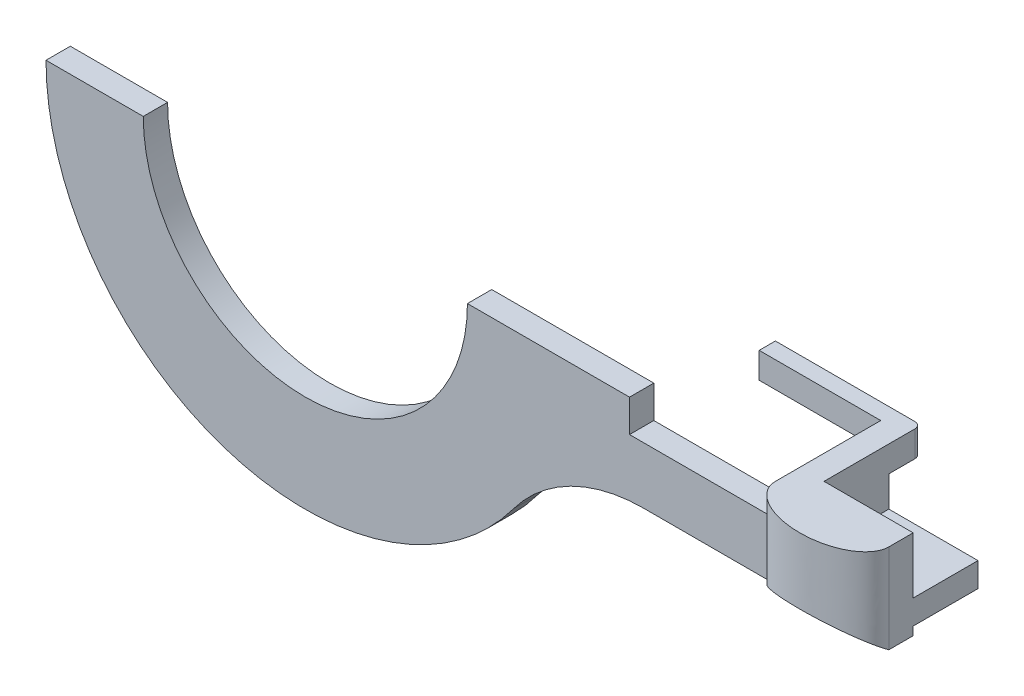
SolidWorks part; units mm, degrees
ref_plane "Face" through (0, 0, 0) normal (0, 0, 1) x (1, 0, 0)
ref_plane "Dessus" through (0, 0, 0) normal (0, 1, 0) x (1, 0, 0)
ref_plane "Droite" through (0, 0, 0) normal (1, 0, 0) x (0, 0, -1)
sketch "Esquisse1" plane through (0, 0, 0) normal (0, 0, 1) x (1, 0, 0)
  line L0 (0, 0) -> (34.0307, 0) construction
  line L1 (10.4373, -2.75) -> (18, -2.75)
  line L2 (10.4373, 2.75) -> (18, 2.75)
  line L3 (18, 2.75) -> (18, -2.75)
  line L4 (10, 1) -> (14.5, 1)
  line L5 (10, -1) -> (14.5, -1)
  line L6 (10, 1) -> (10, -1)
  line L7 (14.5, 1) -> (14.5, -1)
  circle A0 centre (0, 0) radius 5
  arc A1 (6.423, 4.7692) -> (6.423, -4.7692) centre (0, 0) ccw
  arc A2 (6.423, 4.7692) -> (10.4373, 2.75) centre (10.4373, 7.75) ccw
  arc A3 (6.423, -4.7692) -> (10.4373, -2.75) centre (10.4373, -7.75) cw
  point P10 (7.5125, 2.75)
  point P13 (7.5125, -2.75)
  dimension "D1" = 10
  dimension "D2" = 16
  dimension "D4" = 5
  dimension "D3" = 18
  dimension "D5" = 2
  dimension "D6" = 3.5
  dimension "D7" = 4.5
  dimension "D8" = 5.5
extrude "Base-Extrusion" add sketch "Esquisse1" along normal blind 0.75
sketch "Esquisse2" plane through (0, 0, 0) normal (0, 1, 0) x (1, 0, 0)
  line L1 (14.5, -0.75) -> (18, -0.75)
  line L2 (16.25, -0.75) -> (16.25, -1.75) construction
  ellipse E0 centre (16.25, -0.75) end of major axis (18, -0.75) minor radius 1 (14.5, -0.75) -> (18, -0.75) ccw
  dimension "D1" = 1
extrude "Boss.-Extru.1" add sketch "Esquisse2" against normal mid plane 5.5
sketch "Esquisse3" plane through (0, 0, 0) normal (0, 0, -1) x (-1, 0, 0)
  line L0 (-14.1992, 0.0087) -> (-18.5439, 0.0087) construction
  line L1 (-18, 2.5087) -> (-14.5, 2.5087)
  line L2 (-14.5, -1) -> (-14.5, 1) construction
  line L3 (-14.5, -2.4913) -> (-14.5, 2.5087)
  line L4 (-18, -2.75) -> (-18, 2.75) construction
  line L5 (-18, -2.4913) -> (-18, -1.7413)
  line L6 (-18, -2.4913) -> (-14.5, -2.4913)
  line L7 (-18, -1.7413) -> (-15.25, -1.7413)
  line L8 (-15.25, -1.7413) -> (-15.25, 1.7587)
  line L9 (-18, 1.7587) -> (-15.25, 1.7587)
  line L10 (-18, 1.7587) -> (-18, 2.5087)
  dimension "D1" = 5
  dimension "D2" = 0.75
extrude "Boss.-Extru.2" add sketch "Esquisse3" along normal blind 2
sketch "Esquisse4" plane through (0, 0, -2) normal (0, 0, -1) x (-1, 0, 0)
  line L0 (-15.25, 1.7587) -> (-15.25, -1.7413) construction
  line L1 (-15.25, 0.8) -> (-15.25, -0.8)
  line L2 (-14.5, -2.4913) -> (-14.5, 2.5087) construction
  line L3 (-14.5, -0.8) -> (-14.5, 0.8)
  line L4 (-16.3754, 0) -> (-12.5349, 0) construction
  line L5 (-15.25, 0.8) -> (-14.5, 0.8)
  line L6 (-15.25, -0.8) -> (-14.5, -0.8)
  dimension "D1" = 1.6
extrude "Boss.-Extru.3" add sketch "Esquisse4" along normal blind 0.5
sketch "Esquisse5" plane through (0, 0, -2.5) normal (0, 0, -1) x (-1, 0, 0)
  line L4 (-14.5, 0.8) -> (-15.25, 0.8)
  line L5 (-15.25, 0.8) -> (-15.25, -0.8)
  line L6 (-15.25, -0.8) -> (-14.5, -0.8)
  line L7 (-14.5, -0.8) -> (-14.5, 0.8)
  line L8 (-10.75, 0.8) -> (-15.25, 0.8)
  line L9 (-15.25, 0.8) -> (-15.25, -0.8)
  line L10 (-15.25, -0.8) -> (-10.75, -0.8)
  line L11 (-10.75, -0.8) -> (-10.75, 0.8)
  dimension "D2" = 4.5
  dimension "D1" = 0
extrude "Boss.-Extru.4" add sketch "Esquisse5" along normal blind 0.5
sketch "Esquisse6" plane through (18, 0, 0) normal (1, 0, 0) x (0, 0, -1)
  line L2 (0, 0) -> (-4.2638, 0) construction
  line L3 (-0.75, 0) -> (0, 0) construction
  line L4 (-2.2925, 1.6497) -> (-2.2925, -1.6497)
  line L6 (-0.75, 2.75) -> (-0.75, 3.5041)
  line L7 (-0.75, 4.7692) -> (-0.75, 2.75) construction
  line L8 (-0.75, 3.5041) -> (-3.2552, 3.5041)
  line L9 (-3.2552, 3.5041) -> (-3.2552, -3.5041)
  line L10 (-0.75, -2.75) -> (-2.2925, -1.6497)
  line L11 (-0.75, 2.75) -> (-2.2925, 1.6497)
  line L12 (-0.75, -3.5041) -> (-3.2552, -3.5041)
  line L13 (-0.75, -2.75) -> (-0.75, -3.5041)
  point P19 (-3.2552, 0)
extrude "Enlèv. mat.-Extru.1" cut sketch "Esquisse6" against normal blind 5
fillet "Congé1" radius 0.2
sketch "Esquisse8" plane through (0, 0, 0) normal (0, 0, -1) x (-1, 0, 0)
  line L1 (-22.9763, 17.7125) -> (12.112, 17.7125)
  line L2 (-22.9763, 17.7125) -> (-22.9763, 0)
  line L3 (-22.9763, 0) -> (12.112, 0)
  line L4 (12.112, 17.7125) -> (12.112, 0)
extrude "Enlèv. mat.-Extru.2" cut sketch "Esquisse8" against normal through all and the other way through all
